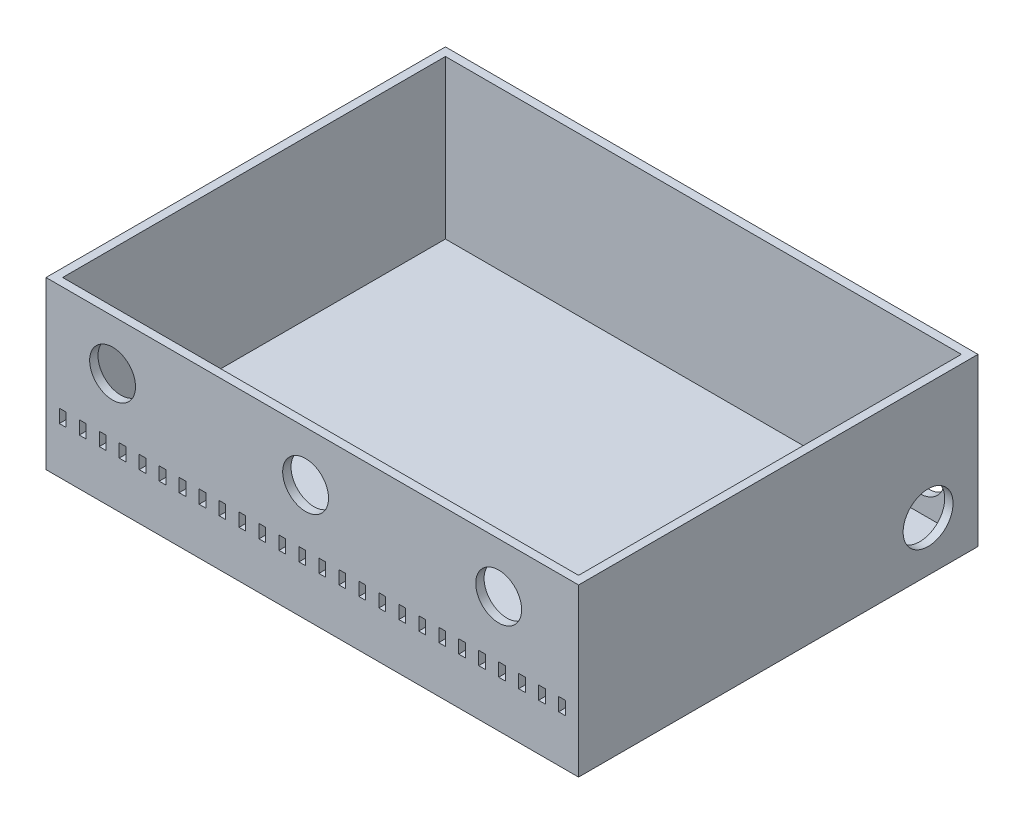
SolidWorks part; units mm, degrees
ref_plane "Front Plane" through (0, 0, 0) normal (0, 0, 1) x (1, 0, 0)
ref_plane "Top Plane" through (0, 0, 0) normal (0, 1, 0) x (1, 0, 0)
ref_plane "Right Plane" through (0, 0, 0) normal (1, 0, 0) x (0, 0, -1)
sketch "Sketch1" plane through (0, 0, 0) normal (0, 1, 0) x (1, 0, 0)
  line L1 (-101.6, -76.2) -> (101.6, -76.2)
  line L2 (-101.6, -76.2) -> (-101.6, 76.2)
  line L3 (-101.6, 76.2) -> (101.6, 76.2)
  line L4 (101.6, -76.2) -> (101.6, 76.2)
  line L5 (-101.6, -76.2) -> (101.6, 76.2) construction
  line L6 (-101.6, 76.2) -> (101.6, -76.2) construction
  point P0 (0, 0)
  dimension "D1" = 203.2
  dimension "D2" = 152.4
extrude "Boss-Extrude1" add sketch "Sketch1" along normal blind 63.5
sketch "Sketch2" plane through (0, 63.5, 0) normal (0, 1, 0) x (1, 0, 0)
  line L0 (-101.6, 76.2) -> (-101.6, -76.2) construction
  line L1 (-98.425, -73.025) -> (98.425, -73.025)
  line L2 (-98.425, -73.025) -> (-98.425, 73.025)
  line L3 (-98.425, 73.025) -> (98.425, 73.025)
  line L4 (98.425, -73.025) -> (98.425, 73.025)
  line L5 (-98.425, -73.025) -> (98.425, 73.025) construction
  line L6 (-98.425, 73.025) -> (98.425, -73.025) construction
  line L7 (101.6, 76.2) -> (-101.6, 76.2) construction
  line L8 (-101.6, -76.2) -> (101.6, -76.2) construction
  point P0 (0, 0)
  dimension "D1" = 3.175
  dimension "D2" = 3.175
  dimension "D3" = 3.175
extrude "Cut-Extrude1" cut sketch "Sketch2" against normal blind 60.325
sketch "Sketch5" plane through (0, 0, 76.2) normal (0, 0, 1) x (1, 0, 0)
  line L0 (-101.6, 63.5) -> (101.6, 63.5) construction
  line L1 (-96.52, 22.86) -> (-93.98, 22.86)
  line L2 (-96.52, 22.86) -> (-96.52, 17.78)
  line L3 (-96.52, 17.78) -> (-93.98, 17.78)
  line L4 (-93.98, 22.86) -> (-93.98, 17.78)
  line L5 (-101.6, 63.5) -> (-101.6, 0) construction
  dimension "D1" = 2.54
  dimension "D2" = 5.08
  dimension "D3" = 40.64
  dimension "D4" = 5.08
extrude "Cut-Extrude3" cut sketch "Sketch5" against normal blind 47.625
pattern_linear "LPattern1" count 26 spacing 7.62 along (1, 0, 0) of "Cut-Extrude3"
sketch "Sketch6" plane through (0, 0, 76.2) normal (0, 0, 1) x (1, 0, 0)
  line L0 (-101.6, 63.5) -> (-101.6, 0) construction
  line L1 (-101.6, 63.5) -> (101.6, 63.5) construction
  circle A0 centre (-76.2, 44.45) radius 8.75
  dimension "D1" = 17.5
  dimension "D2" = 25.4
  dimension "D3" = 19.05
extrude "Cut-Extrude4" cut sketch "Sketch6" against normal blind 47.625
pattern_linear "LPattern2" count 3 spacing 73.66 along (1, 0, 0) of "Cut-Extrude4"
sketch "Sketch7" plane through (101.6, 0, 0) normal (1, 0, 0) x (0, 0, -1)
  line L0 (-76.2, 0) -> (76.2, 0) construction
  line L1 (76.2, 63.5) -> (76.2, 0) construction
  circle A0 centre (57.15, 19.05) radius 9.525
  dimension "D1" = 19.05
  dimension "D2" = 19.05
  dimension "D3" = 19.05
extrude "Cut-Extrude6" cut sketch "Sketch7" against normal blind 47.625
sketch "Sketch8" plane through (0, 0, -76.2) normal (0, 0, -1) x (-1, 0, 0)
  line L0 (-101.6, 63.5) -> (-101.6, 0) construction
  line L1 (-101.6, 0) -> (101.6, 0) construction
  circle A0 centre (-82.55, 19.05) radius 9.525
  dimension "D1" = 19.05
  dimension "D3" = 19.05
  dimension "D2" = 19.05
extrude "Cut-Extrude7" cut sketch "Sketch8" against normal blind 47.625
